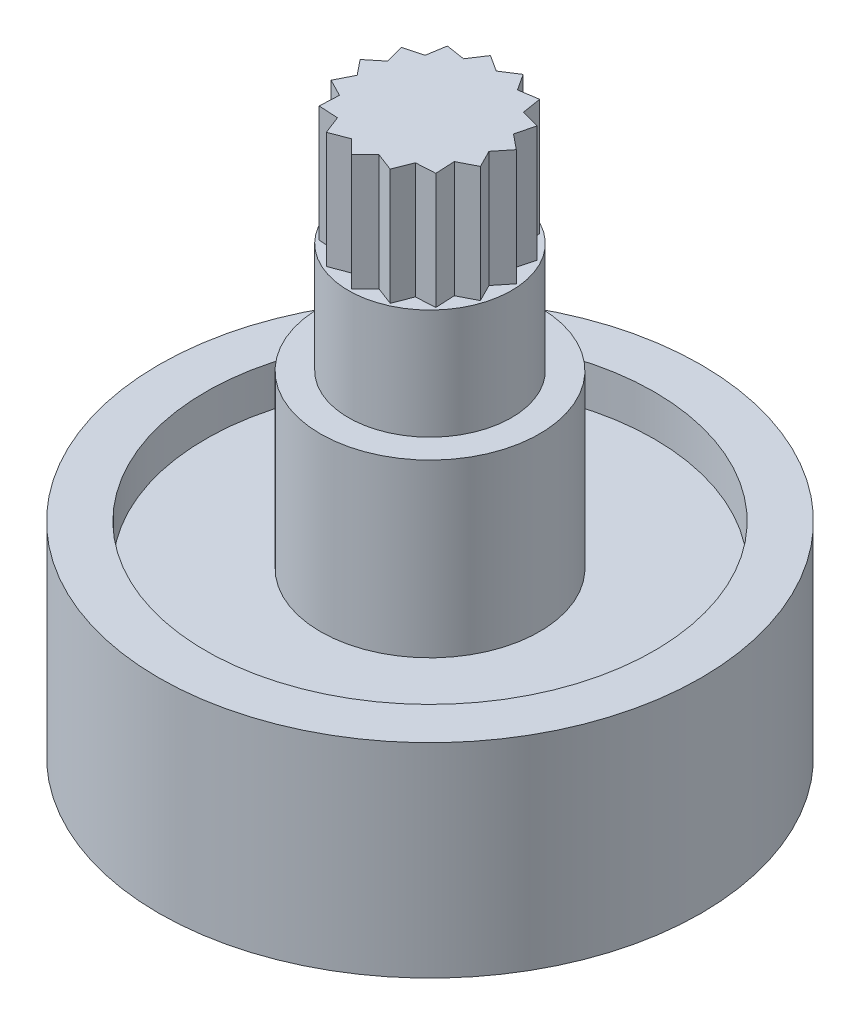
SolidWorks part; units mm, degrees
material "Nylon 101"
ref_plane "Front Plane" through (0, 0, 0) normal (0, 0, 1) x (1, 0, 0)
ref_plane "Top Plane" through (0, 0, 0) normal (0, 1, 0) x (1, 0, 0)
ref_plane "Right Plane" through (0, 0, 0) normal (1, 0, 0) x (0, 0, -1)
sketch "Sketch1" plane through (0, 0, 0) normal (0, 0, 1) x (1, 0, 0)
  line L0 (0, 0) -> (0, 27.5) construction
  line L1 (13.3, 0) -> (13.3, 10)
  line L2 (13.3, 10) -> (11, 10)
  line L3 (11, 10) -> (11, 8)
  line L4 (11, 8) -> (5.375, 8)
  line L5 (5.375, 8) -> (5.375, 16.4)
  line L6 (5.375, 16.4) -> (4, 16.4)
  line L7 (4, 16.4) -> (4, 21.8)
  line L8 (4, 21.8) -> (3.85, 21.8)
  line L9 (3.85, 21.8) -> (3.85, 27.5)
  line L10 (3.85, 27.5) -> (0, 27.5)
  line L11 (0, 14.75) -> (0, 27.5)
  line L12 (0, 14.75) -> (3.55, 14.75)
  line L13 (3.55, 14.75) -> (3.55, 3.5)
  line L14 (3.55, 3.5) -> (7, 3.5)
  line L15 (7, 3.5) -> (7, 0)
  line L16 (7, 0) -> (13.3, 0)
  dimension "D1" = 10
  dimension "D2" = 6.4
  dimension "D3" = 2
  dimension "D4" = 5.4
  dimension "D5" = 27.5
  dimension "D6" = 7.7
  dimension "D7" = 8
  dimension "D8" = 7.1
  dimension "D9" = 14.75
  dimension "D10" = 14
  dimension "D11" = 3.5
  dimension "D12" = 10.75
  dimension "D13" = 22
  dimension "D14" = 26.6
revolve "52 Tooth" add sketch "Sketch1" angle 360 about L0
sketch "Sketch2" plane through (0, 27.5, 0) normal (0, 1, 0) x (1, 0, 0)
  line L0 (-0.8005, 3.7659) -> (0, 3.25)
  line L1 (0, 3.25) -> (0.8005, 3.7659)
  line L2 (0, 0) -> (-0.8005, 3.7659) construction
  line L3 (0, 0) -> (0, 3.25) construction
  line L4 (0, 0) -> (0.8005, 3.7659) construction
  circle A0 centre (0, 0) radius 3.85 construction
  circle A1 centre (0, 0) radius 3.85
  circle A2 centre (0, 0) radius 3.25
  circle M1 centre (0, 0) radius 3.85
  dimension "D3" = 6.5
  dimension "D1" = 24
  dimension "D2" = 12
extrude "Cut-Extrude1" cut sketch "Sketch2" against normal up to surface (5.7 mm away) contours L0 L1 M1 up to face at (0, 21.8, -3.85)
pattern_circular "CirPattern1" count 15 over 360 about axis through (0, 0, 0) along (0, 1, 0) of "Cut-Extrude1"
